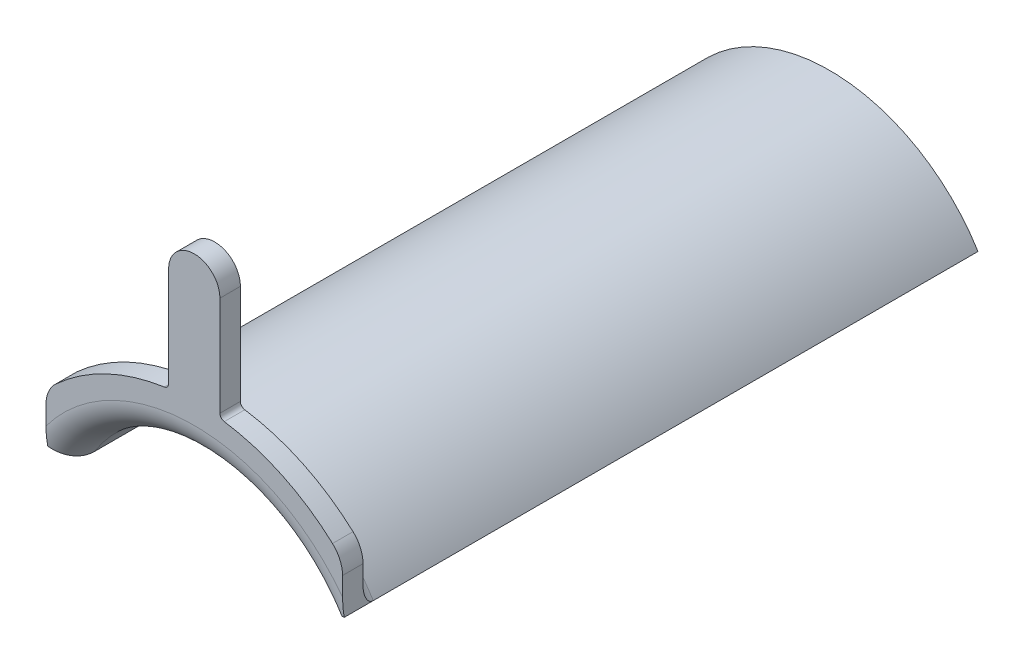
SolidWorks part; units mm, degrees
material "Медь"
ref_plane "Спереди" through (0, 0, 0) normal (0, 0, 1) x (1, 0, 0)
ref_plane "Сверху" through (0, 0, 0) normal (0, 1, 0) x (1, 0, 0)
ref_plane "Справа" through (0, 0, 0) normal (1, 0, 0) x (0, 0, -1)
sketch "Эскиз1" plane through (0, 0, 0) normal (0, 0, 1) x (1, 0, 0)
  line L0 (0, 0) -> (0.866, 0.5) construction
  line L12 (-1.2733, 0.7929) -> (-1.4466, 0.8929)
  line L13 (1.2733, 0.7929) -> (1.4466, 0.8929)
  circle A4 centre (0, 0) radius 1 construction
  arc A36 (1.4466, 0.8929) -> (-1.4466, 0.8929) centre (0, 0) ccw
  arc A37 (1.2733, 0.7929) -> (-1.2733, 0.7929) centre (0, 0) ccw construction
  arc A41 (1.2733, 0.7929) -> (-1.2733, 0.7929) centre (0, 0) ccw
  point P27 (0, 0)
  dimension "D1" = 2
  dimension "D2" = 0.2001
  dimension "D5" = 2.8932
  dimension "D6" = 2.5466
  dimension "D3" = 1.5
  dimension "D4" = 1.7
extrude "Бобышка-Вытянуть6" add sketch "Эскиз1" along normal blind 6
sketch "Эскиз8" plane through (0, 0, 6) normal (0, 0, 1) x (1, 0, 0)
  line L0 (-1.2733, 0.7929) -> (-1.4466, 0.8929)
  line L1 (1.2733, 0.7929) -> (1.4466, 0.8929)
  line L2 (-1.4466, 0.8929) -> (-1.4466, 1.3811)
  line L3 (1.4466, 0.8929) -> (1.4466, 1.3811)
  arc A0 (-1.2733, 0.7929) -> (1.2733, 0.7929) centre (0, 0) cw
  arc A2 (1.4466, 1.3811) -> (-1.4466, 1.3811) centre (0, 0) ccw
  dimension "D1" = 4
  dimension "D2" = 2.8932
extrude "Бобышка-Вытянуть7" add sketch "Эскиз8" along normal blind 0.2
sketch "Эскиз9" plane through (0, 0, 6.2) normal (0, 0, 1) x (1, 0, 0)
  line L0 (0, 0.0105) -> (0, 2.6903) construction
  line L1 (-0.25, 1.9843) -> (-0.25, 3)
  line L2 (0.25, 1.9843) -> (0.25, 3)
  arc A0 (1.4466, 1.3811) -> (-1.4466, 1.3811) centre (0, 0) ccw construction
  arc A1 (0.25, 1.9843) -> (-0.25, 1.9843) centre (0, 0) ccw
  arc A2 (-0.25, 3) -> (0.25, 3) centre (0, 3) cw
  point P12 (0, 0)
  dimension "D1" = 0.5
  dimension "D2" = 3
extrude "Бобышка-Вытянуть8" add sketch "Эскиз9" against normal blind 0.2
fillet "Скругление4" radius 0.05 2 edges at (0.25, 1.9843, 6.1) (-0.25, 1.9843, 6.1)
fillet "Скругление5" radius 0.1 1 edges at (0, 1.7, 6)
fillet "Скругление6" radius 0.3 1 edges at (0, 1.5, 6.2)
fillet "Скругление7" radius 0.3 2 edges at (-1.4466, 1.3811, 6.1) (1.4466, 1.3811, 6.1)
